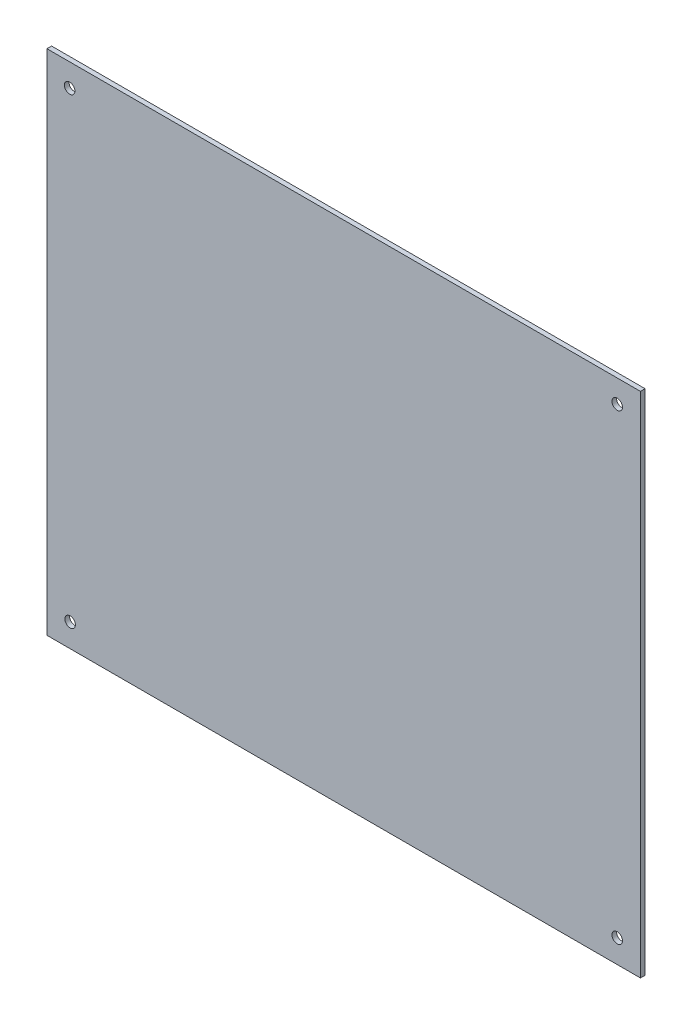
SolidWorks part; units mm, degrees
ref_plane "Front Plane" through (0, 0, 0) normal (0, 0, 1) x (1, 0, 0)
ref_plane "Top Plane" through (0, 0, 0) normal (0, 1, 0) x (1, 0, 0)
ref_plane "Right Plane" through (0, 0, 0) normal (1, 0, 0) x (0, 0, -1)
sketch "Sketch1" plane through (0, 0, 0) normal (0, 0, 1) x (1, 0, 0)
  line L1 (0, 0) -> (243.332, 0)
  line L2 (0, 0) -> (0, 208.28)
  line L3 (0, 208.28) -> (243.332, 208.28)
  line L11 (243.332, 0) -> (243.332, 208.28)
  dimension "D1" = 208.28
  dimension "D7" = 243.332
extrude "Boss-Extrude1" add sketch "Sketch1" along normal blind 1.905
sketch "Sketch4" plane through (0, 0, 1.905) normal (0, 0, 1) x (1, 0, 0)
  line L2 (233.807, 198.955) -> (243.332, 198.955) construction
  line L3 (243.332, 0) -> (243.332, 208.28) construction
  line L4 (233.807, 198.955) -> (233.807, 208.48) construction
  line L6 (0, 208.48) -> (243.332, 208.48) construction
  line L7 (0, 198.955) -> (9.325, 198.955) construction
  line L8 (0, 208.28) -> (0, 0) construction
  line L9 (9.325, 198.955) -> (9.325, 208.28) construction
  line L10 (243.332, 208.28) -> (0, 208.28) construction
  line L11 (0, 9.525) -> (9.525, 9.525) construction
  line L12 (9.525, 9.525) -> (9.525, 0) construction
  line L13 (0, 0) -> (243.332, 0) construction
  line L14 (233.807, 0) -> (233.807, 9.525) construction
  line L15 (233.807, 9.525) -> (243.332, 9.525) construction
  line L16 (243.332, 0) -> (243.332, 208.28) construction
  line L17 (0, 0) -> (243.332, 0) construction
  point P0 (9.325, 198.955)
  point P1 (233.807, 198.955)
  point P2 (233.807, 9.525)
  point P3 (9.525, 9.525)
  point P13 (233.807, 198.955)
  dimension "D2" = 9.525
hole_wizard "#6 Clearance Hole1" positions "Sketch4" profile "Sketch5" hole size "#6" standard "ANSI Inch" end condition up to next
sketch "Sketch5" plane through (9.325, 198.955, 1.905) normal (1, 0, 0) x (0, -1, 0)
  line L0 (0, 0) -> (0, 1.905)
  line L1 (0, 1.905) -> (2.1526, 1.905)
  line L2 (2.1526, 1.905) -> (2.1526, 0)
  line L5 (2.1526, 0) -> (0, 0)
  line L11 (0, -6.35) -> (0, 107.95) construction
  dimension "Thru Hole Dia." = 4.3053
  dimension "Thru Hole Depth" = 1.905
